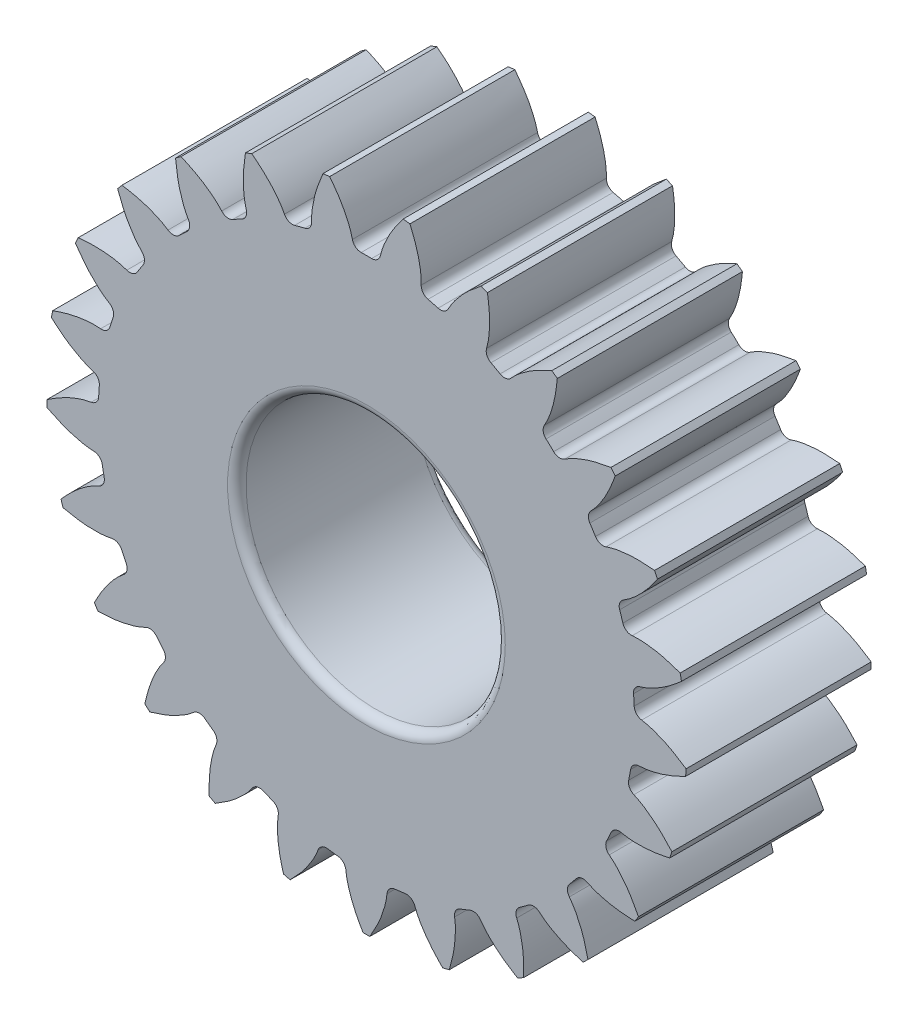
SolidWorks part; units mm, degrees
ref_plane "前视基准面" through (0, 0, 0) normal (0, 0, 1) x (1, 0, 0)
ref_plane "上视基准面" through (0, 0, 0) normal (0, 1, 0) x (1, 0, 0)
ref_plane "右视基准面" through (0, 0, 0) normal (1, 0, 0) x (0, 0, -1)
ref_axis "基准轴1" through (0, 0, -88.99) along (0, 0, 1)
sketch "草图1" plane through (0, 0, 0) normal (0, 0, 1) x (1, 0, 0)
  circle A0 centre (0, 0) radius 34.575
extrude "凸台-拉伸1" add sketch "草图1" along normal blind 20
sketch "草图2" plane through (0, 0, 0) normal (0, 0, -1) x (-1, 0, 0)
  arc A0 (0.5647, 28.9445) -> (-0.5647, 28.9445) centre (0, 0) ccw
  circle A1 centre (0, 0) radius 34.575
  arc A2 (3.9686, 34.3465) -> (-3.9686, 34.3465) centre (0, 0) ccw
  arc A3 (0.5647, 28.9445) -> (1.5123, 29.6963) centre (0.5832, 29.8943) ccw
  arc A4 (-0.5647, 28.9445) -> (-1.5123, 29.6963) centre (-0.5832, 29.8943) cw
  spline S0 degree 3 poles (1.5123, 29.6963) (1.5303, 29.7807) (1.6151, 30.119) (1.837, 30.8013) (2.2888, 31.8086) (2.9901, 33.0443) (3.6214, 33.8844) (3.9686, 34.3465) knots 0.129473 0.129473 0.129473 0.129473 0.17198 0.301359 0.482488 0.715369 1 1 1 1
  spline S1 degree 3 poles (-1.5123, 29.6963) (-1.5303, 29.7807) (-1.6151, 30.119) (-1.837, 30.8013) (-2.2888, 31.8086) (-2.9901, 33.0443) (-3.6214, 33.8844) (-3.9686, 34.3465) knots 0.129473 0.129473 0.129473 0.129473 0.17198 0.301359 0.482488 0.715369 1 1 1 1
  point P0 (1.4562, 29.3293)
  point P1 (1.4748, 29.4857)
  point P2 (1.5736, 29.9476)
  point P3 (1.8154, 30.697)
  point P4 (2.2594, 31.706)
  point P5 (2.9608, 32.9376)
  point P6 (3.9686, 34.3465)
  point P7 (-0.0283, 28.95)
  dimension "D2" = 0.95
  dimension "D3" = 0.95
  dimension "D1" = 0
extrude "切除-拉伸1" cut sketch "草图2" against normal blind 20
pattern_circular "阵列(圆周)1" count 25 over 360 about axis through (0, 0, -88.99) along (0, 0, 1) of "切除-拉伸1"
sketch "草图3" plane through (0, 0, 20) normal (0, 0, 1) x (1, 0, 0)
  circle A0 centre (0, 0) radius 14
extrude "切除-拉伸2" cut sketch "草图3" against normal through all
fillet "圆角1" radius 1 2 edges at (14, 0, 0) (14, 0, 20)
ref_plane "BaseFace1" through (0, 0, 0) normal (0, 0, -1) x (-1, 0, 0)
ref_plane "BaseFace2" through (0, 0, 20) normal (0, 0, 1) x (1, 0, 0)
ref_plane "中间基准面" through (0, 0, 10) normal (0, 0, -1) x (-1, 0, 0)
